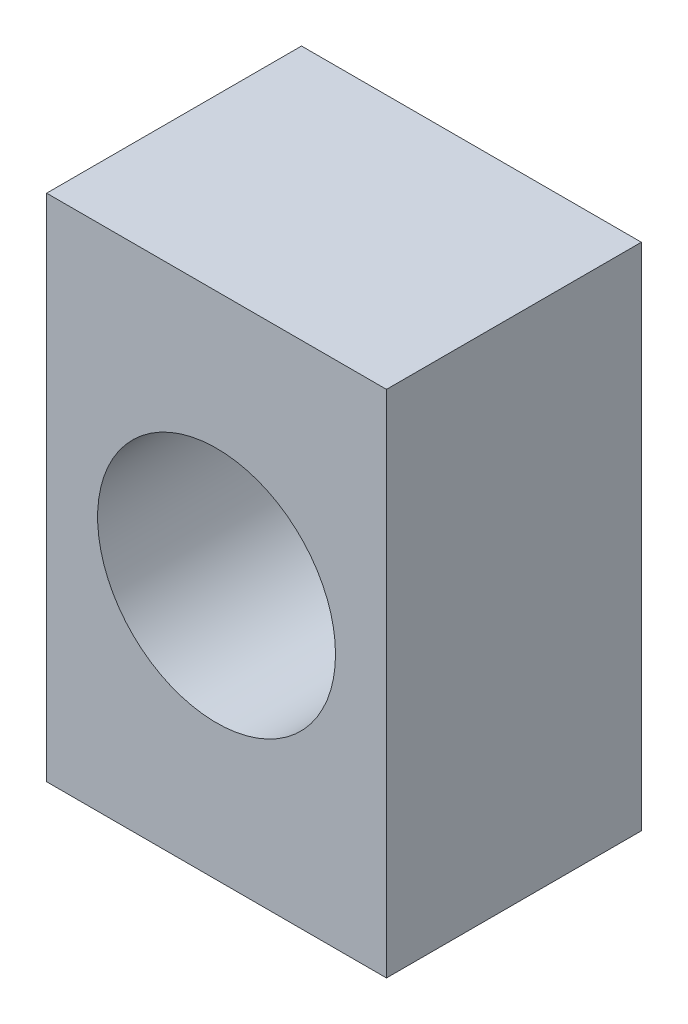
SolidWorks part; units mm, degrees
ref_plane "Front Plane" through (0, 0, 0) normal (0, 0, 1) x (1, 0, 0)
ref_plane "Top Plane" through (0, 0, 0) normal (0, 1, 0) x (1, 0, 0)
ref_plane "Right Plane" through (0, 0, 0) normal (1, 0, 0) x (0, 0, -1)
sketch "Sketch1" plane through (0, 0, 0) normal (0, 0, 1) x (1, 0, 0)
  line L0 (-20, 30) -> (-20, -30)
  line L1 (-20, -30) -> (20, -30)
  line L2 (20, -30) -> (20, 30)
  line L3 (20, 30) -> (-20, 30)
  line L4 (-20, 30) -> (0, 0) construction
  line L5 (0, 0) -> (20, -30) construction
  line L6 (20, 30) -> (0, 0) construction
  line L7 (-20, -30) -> (0, 0) construction
  circle A0 centre (0, 0) radius 14
  circle A1 centre (0, 0) radius 18 construction
  dimension "D1" = 28
  dimension "D2" = 4
  dimension "D3" = 40
  dimension "D4" = 60
extrude "Boss-Extrude1" add sketch "Sketch1" along normal blind 27
sketch "Sketch2" plane through (0, 0, 0) normal (0, 0, -1) x (-1, 0, 0)
  line L4 (20, 30) -> (-20, 30)
  line L5 (-20, 30) -> (-20, -30)
  line L6 (-20, -30) -> (20, -30)
  line L7 (20, -30) -> (20, 30)
  line L8 (20, 30) -> (-20, 30)
  line L9 (-20, 30) -> (-20, -30)
  line L10 (-20, -30) -> (20, -30)
  line L11 (20, -30) -> (20, 30)
  circle A0 centre (0, 0) radius 13
  dimension "D1" = 26
  dimension "D2" = 0
extrude "Boss-Extrude2" add sketch "Sketch2" along normal blind 3
